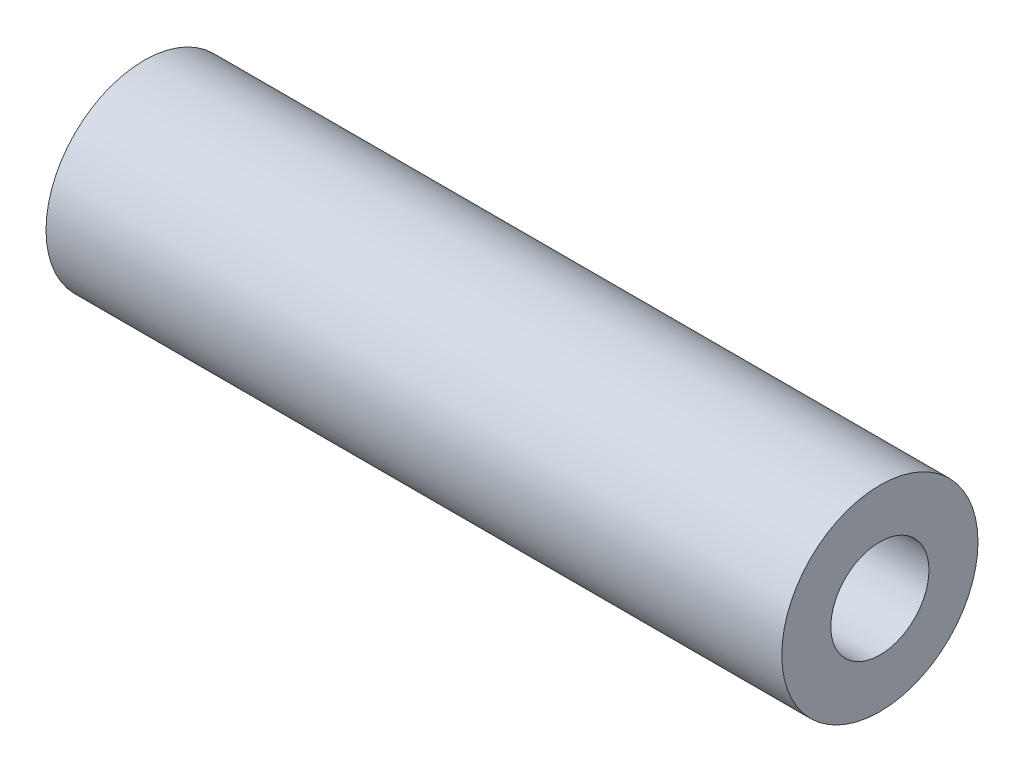
SolidWorks part; units mm, degrees
material "7075-T6 (SN)"
ref_plane "Front Plane" through (0, 0, 0) normal (0, 0, 1) x (1, 0, 0)
ref_plane "Top Plane" through (0, 0, 0) normal (0, 1, 0) x (1, 0, 0)
ref_plane "Right Plane" through (0, 0, 0) normal (1, 0, 0) x (0, 0, -1)
sketch "Sketch1" plane through (0, 0, 0) normal (1, 0, 0) x (0, 0, -1)
  circle A0 centre (0, 0) radius 6.35
  circle A1 centre (0, 0) radius 3.175
  dimension "D1" = 6.35
  dimension "D2" = 12.7
extrude "Boss-Extrude1" add sketch "Sketch1" along normal blind 47.625
